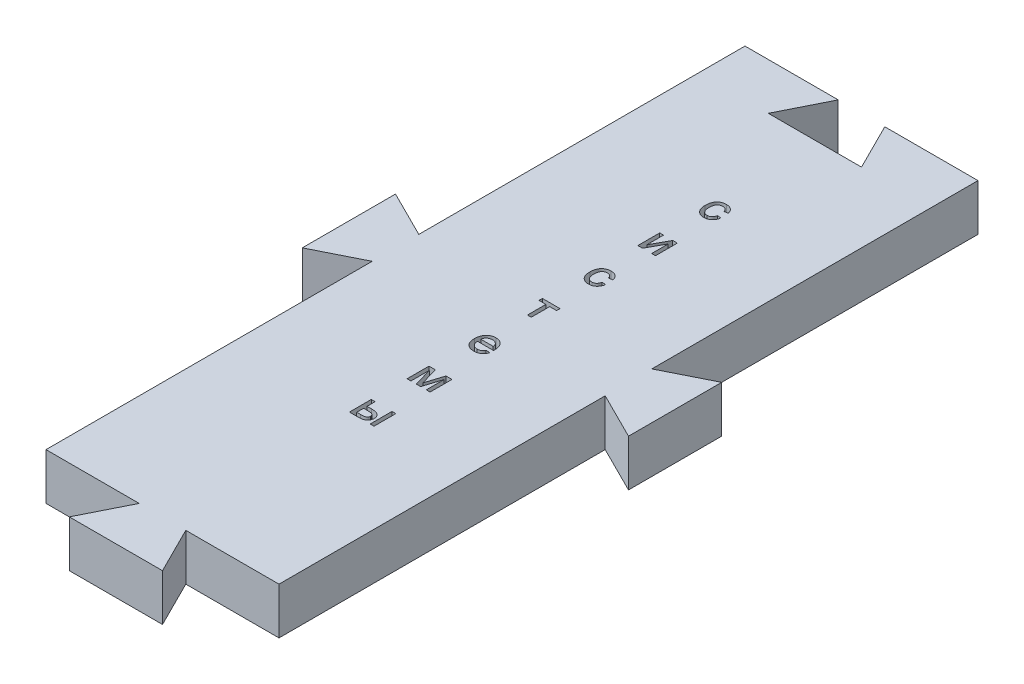
SolidWorks part; units mm, degrees
ref_plane "Спереди" through (0, 0, 0) normal (0, 0, 1) x (1, 0, 0)
ref_plane "Сверху" through (0, 0, 0) normal (0, 1, 0) x (1, 0, 0)
ref_plane "Справа" through (0, 0, 0) normal (1, 0, 0) x (0, 0, -1)
sketch "Эскиз1" plane through (0, 0, 0) normal (0, 1, 0) x (1, 0, 0)
  line L0 (10, 42.5) -> (2, 42.5)
  line L1 (10, -17.5) -> (2, -17.5)
  line L2 (10, -17.5) -> (10, 10.5)
  line L3 (-4, 38.5) -> (4, 38.5)
  line L4 (-10, -17.5) -> (-10, 10.5)
  line L5 (-4, -21.5) -> (4, -21.5)
  line L6 (4, -21.5) -> (2, -17.5)
  line L7 (-4, -21.5) -> (-2, -17.5)
  line L8 (-2, -17.5) -> (-10, -17.5)
  line L9 (4, 38.5) -> (2, 42.5)
  line L10 (-4, 38.5) -> (-2, 42.5)
  line L11 (-2, 42.5) -> (-10, 42.5)
  line L12 (-14, 16.5) -> (-14, 8.5)
  line L13 (-14, 8.5) -> (-10, 10.5)
  line L14 (-14, 16.5) -> (-10, 14.5)
  line L15 (-10, 14.5) -> (-10, 42.5)
  line L16 (0, -12.2343) -> (0, 16.5) construction
  line L17 (14, 16.5) -> (10, 14.5)
  line L18 (14, 16.5) -> (14, 8.5)
  line L19 (14, 8.5) -> (10, 10.5)
  line L20 (10, 14.5) -> (10, 42.5)
  point P6 (-10, 42.5)
  dimension "D2" = 20
  dimension "D3" = 60
  dimension "D4" = 8
  dimension "D6" = 4
extrude "Бобышка-Вытянуть1" add sketch "Эскиз1" along normal blind 4 contours L4 L13 L12 L14 L15 L11 L10 L3 L9 L0 L20 L17 L18 L19 L2 L1 L6 L5 L7 L8
sketch "Эскиз2" plane through (0, 0, 0) normal (0, 1, 0) x (1, 0, 0)
  text T0 "с\r\nи\r\nс\r\nт\r\nе\r\nм\r\nы\r\n" font "Arial" height in points 10
  point P1 (0, 35.7713)
  point P2 (0, 28.0219)
extrude "Вырез-Вытянуть2" cut sketch "Эскиз2" along normal through all
